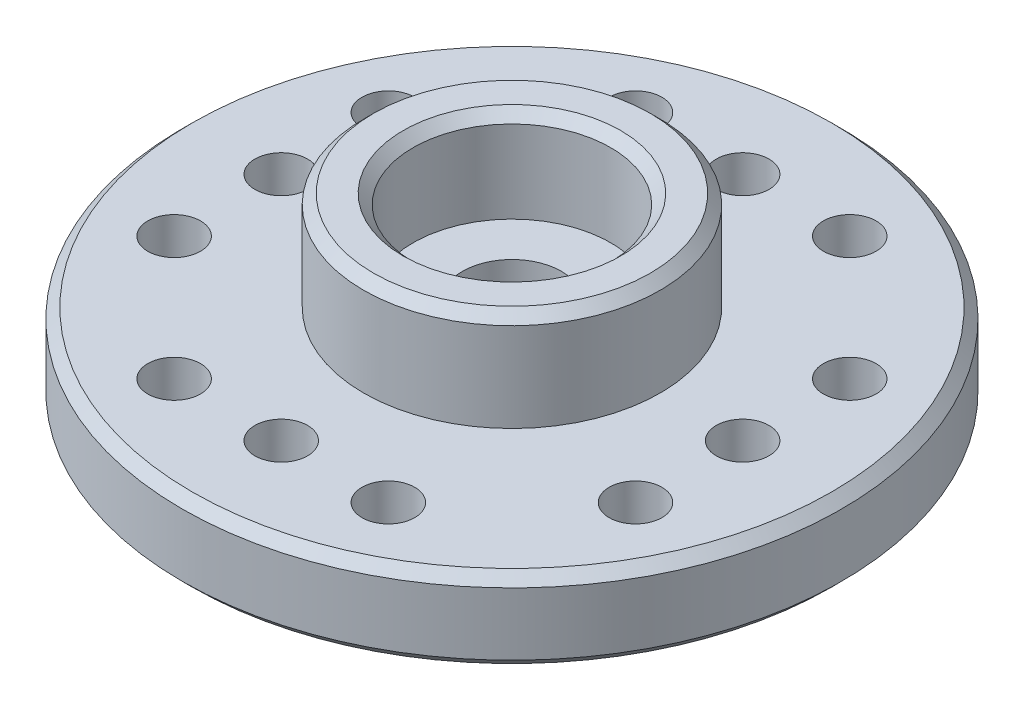
SolidWorks part; units mm, degrees
ref_plane "前视基准面" through (0, 0, 0) normal (0, 0, 1) x (1, 0, 0)
ref_plane "上视基准面" through (0, 0, 0) normal (0, 1, 0) x (1, 0, 0)
ref_plane "右视基准面" through (0, 0, 0) normal (1, 0, 0) x (0, 0, -1)
sketch "草图1" plane through (0, 0, 0) normal (0, 1, 0) x (1, 0, 0)
  circle A0 centre (0, 0) radius 10
  dimension "D1" = 20
extrude "凸台-拉伸1" add sketch "草图1" along normal blind 2.5
sketch "草图2" plane through (0, 2.5, 0) normal (0, 1, 0) x (1, 0, 0)
  circle A0 centre (0, 0) radius 4.5
  dimension "D1" = 9
extrude "凸台-拉伸2" add sketch "草图2" along normal blind 3
sketch "草图3" plane through (0, 5.5, 0) normal (0, 1, 0) x (1, 0, 0)
  circle A0 centre (0, 0) radius 3
  dimension "D1" = 6
extrude "切除-拉伸1" cut sketch "草图3" against normal blind 2.8
sketch "草图4" plane through (0, 0, 0) normal (0, -1, 0) x (1, 0, 0)
  line L0 (0, 0) -> (0, 7) construction
  line L1 (-1000, 7) -> (49000, 7) construction
  circle A0 centre (0, 0) radius 7 construction
  circle A1 centre (0, 7) radius 0.8
  circle A5 centre (0, 0) radius 1.5
  circle A6 centre (-3.25, 7) radius 0.8
  circle A7 centre (3.25, 7) radius 0.8
  circle A8 centre (7, 0) radius 0.8
  circle A9 centre (7, 3.25) radius 0.8
  circle A10 centre (7, -3.25) radius 0.8
  circle A11 centre (0, -7) radius 0.8
  circle A12 centre (3.25, -7) radius 0.8
  circle A13 centre (-3.25, -7) radius 0.8
  circle A14 centre (-7, 0) radius 0.8
  circle A15 centre (-7, -3.25) radius 0.8
  circle A16 centre (-7, 3.25) radius 0.8
  point P8 (6.9144, -1.0911)
  point P9 (0, 0)
  point P14 (0, 0)
  point P34 (0, 0)
  dimension "D1" = 14
  dimension "D2" = 1.6
  dimension "D4" = 3
  dimension "D5" = 1.6
  dimension "D7" = 1.6
  dimension "D6" = 3.25
  dimension "D8" = 3.25
  dimension "D3" = 4
extrude "切除-拉伸2" cut sketch "草图4" against normal through all
chamfer "倒角1" distance 0.3 angle 45 4 edges at (0, 0, 10) (0, 2.5, 10) (0, 5.5, 4.5) (0, 5.5, 3)
sketch "草图5" plane through (0, 0, 0) normal (0, -1, 0) x (1, 0, 0)
  circle A0 centre (0, 0) radius 3
  circle A1 centre (0, 0) radius 3.5
  circle A2 centre (0, 0) radius 4.5
  point P6 (-0.0825, 0)
  circle M7 centre (0, 0) radius 1.5
  dimension "D1" = 6
  dimension "D2" = 7
  dimension "D3" = 9
extrude "切除-拉伸3" cut sketch "草图5" against normal blind 1 contours A0 M7 | A2 A1
